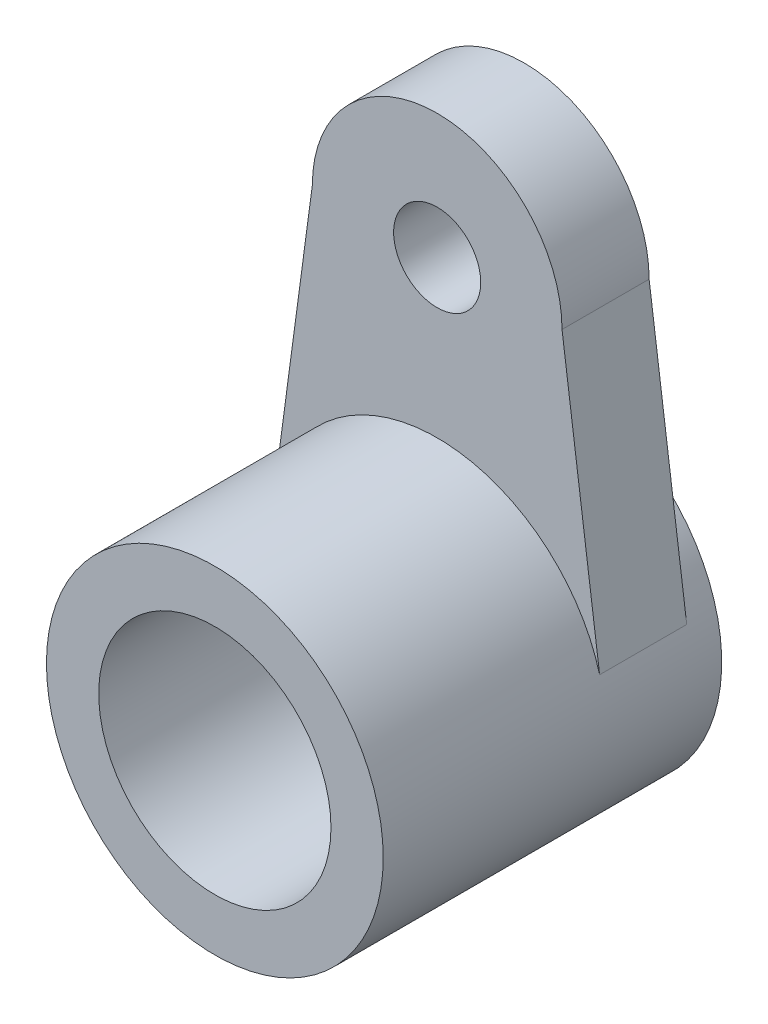
SolidWorks part; units mm, degrees
ref_plane "前视基准面" through (0, 0, 0) normal (0, 0, 1) x (1, 0, 0)
ref_plane "上视基准面" through (0, 0, 0) normal (0, 1, 0) x (1, 0, 0)
ref_plane "右视基准面" through (0, 0, 0) normal (1, 0, 0) x (0, 0, -1)
other "Configuration Table"
sketch "草图1" plane through (0, 0, 0) normal (0, 0, 1) x (1, 0, 0)
  line L1 (-2.15, 0) -> (-2.7974, -4.8256)
  line L2 (2.15, 0) -> (2.7974, -4.8256)
  arc A0 (2.15, 0) -> (-2.15, 0) centre (0, 0) ccw
  arc A1 (-2.7974, -4.8256) -> (2.7974, -4.8256) centre (0, -5.59) ccw
extrude "凸台-拉伸1" add sketch "草图1" along normal blind 1.5
sketch "草图3" plane through (0, 0, 1.5) normal (0, 0, 1) x (1, 0, 0)
  circle A0 centre (0, -5.59) radius 2.9
extrude "凸台-拉伸2" add sketch "草图3" along normal blind 3.829
sketch "草图4" plane through (0, 0, 0) normal (0, 0, -1) x (-1, 0, 0)
  circle A0 centre (0, -5.59) radius 2.9
extrude "凸台-拉伸3" add sketch "草图4" along normal blind 0.5
sketch "草图5" plane through (0, 0, 5.329) normal (0, 0, 1) x (1, 0, 0)
  circle A0 centre (0, -5.59) radius 2
extrude "切除-拉伸1" cut sketch "草图5" against normal blind 3
sketch "草图6" plane through (0, 0, -0.5) normal (0, 0, -1) x (-1, 0, 0)
  circle A0 centre (0, -5.59) radius 2
extrude "切除-拉伸2" cut sketch "草图6" against normal blind 0.7
sketch "草图7" plane through (0, 0, 0.2) normal (0, 0, -1) x (-1, 0, 0)
  circle A0 centre (0, -5.59) radius 1.1
extrude "切除-拉伸3" cut sketch "草图7" against normal blind 3.7
sketch "草图8" plane through (0, 0, 1.5) normal (0, 0, 1) x (1, 0, 0)
  circle A0 centre (0, 0) radius 0.75
extrude "切除-拉伸4" cut sketch "草图8" against normal blind 3.7
sketch "草图9" plane through (0, 0, 0) normal (0, 0, -1) x (-1, 0, 0)
  circle A0 centre (0, 0) radius 1.1476
